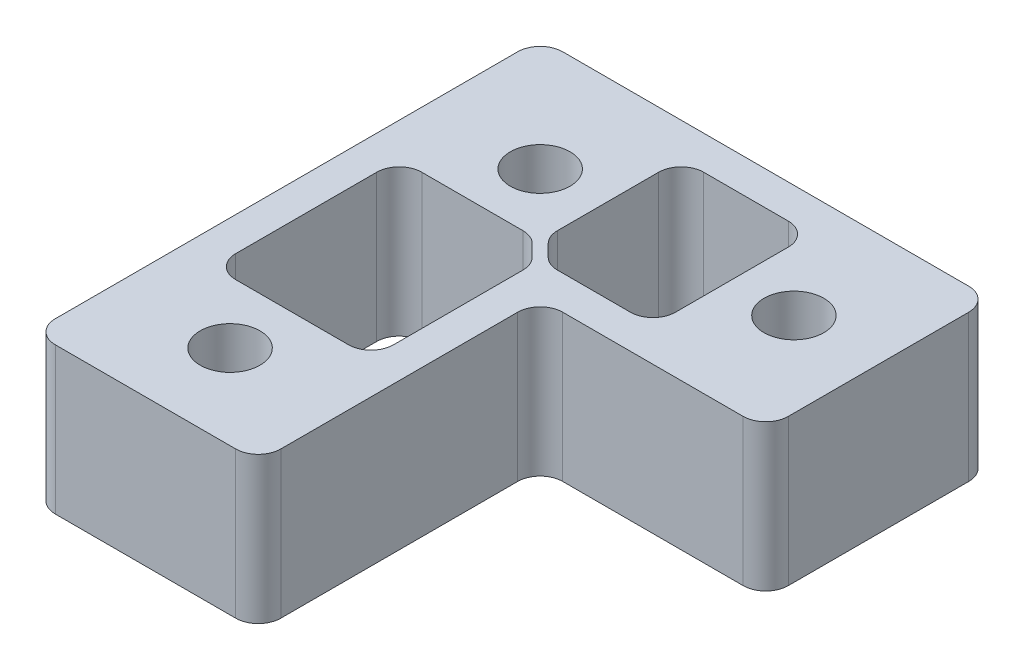
SolidWorks part; units mm, degrees
ref_plane "Front Plane" through (0, 0, 0) normal (0, 0, 1) x (1, 0, 0)
ref_plane "Top Plane" through (0, 0, 0) normal (0, 1, 0) x (1, 0, 0)
ref_plane "Right Plane" through (0, 0, 0) normal (1, 0, 0) x (0, 0, -1)
sketch "Sketch1" plane through (0, 0, 0) normal (0, 1, 0) x (1, 0, 0)
  line L0 (0, 0) -> (0, -2.65) construction
  line L2 (-10, 10) -> (-10, -35)
  line L3 (-10, -35) -> (10, -35)
  line L4 (10, -10) -> (10, -35)
  line L5 (-10, 10) -> (30, 10)
  line L7 (10, -10) -> (30, -10)
  line L8 (30, 10) -> (30, -10)
  line L9 (0, 0) -> (2.65, 0) construction
  line L10 (0, -30.15) -> (0, -35) construction
  line L11 (25.15, 0) -> (30, 0) construction
  circle A0 centre (0, 0) radius 2.65
  circle A1 centre (0, -27.5) radius 2.65
  circle A2 centre (22.5, 0) radius 2.65
  dimension "D4" = 5.3
  dimension "D1" = 20
  dimension "D2" = 45
  dimension "D3" = 40
  dimension "D5" = 7.5
extrude "Boss-Extrude1" add sketch "Sketch1" along normal blind 13
sketch "Sketch2" plane through (0, 13, 0) normal (0, 1, 0) x (1, 0, 0)
  line L0 (-7, -22) -> (-10, -22) construction
  line L1 (-7, -5.5) -> (4.7929, -5.5)
  line L2 (-7, -5.5) -> (-7, -22)
  line L3 (-7, -22) -> (7, -22)
  line L4 (7, -7.7071) -> (7, -22)
  line L5 (17, 7) -> (5.5, 7)
  line L6 (17, 7) -> (17, -7)
  line L7 (17, -7) -> (7.7071, -7)
  line L8 (5.5, 7) -> (5.5, -4.7929)
  line L9 (-10, 10) -> (-10, -35) construction
  line L10 (7, -22) -> (10, -22) construction
  line L11 (10, -35) -> (10, -10) construction
  line L12 (17, -7) -> (17, -10) construction
  line L13 (10, -10) -> (30, -10) construction
  line L14 (0, -27.5) -> (0, -22) construction
  line L15 (22.5, 0) -> (17, 0) construction
  line L16 (0, 0) -> (0, -5.5) construction
  line L17 (0, 0) -> (5.5, 0) construction
  line L18 (4.7929, -5.5) -> (7, -7.7071)
  line L19 (5.5, -4.7929) -> (7.7071, -7)
  line L20 (5.5, -4.7929) -> (4.7929, -5.5) construction
  line L21 (7.7071, -7) -> (7, -7.7071) construction
  point P26 (4.6465, -5.5)
  dimension "D1" = 3
  dimension "D2" = 5.5
  dimension "D3" = 1
  dimension "D4" = 180
extrude "Cut-Extrude1" cut sketch "Sketch2" against normal through all
fillet "Fillet1" radius 2 16 edges at (17, 6.5, 7) (7, 6.5, 22) (-7, 6.5, 22) (5.5, 6.5, -7) (-7, 6.5, 5.5) (17, 6.5, -7) (-10, 6.5, -10) (30, 6.5, -10) (30, 6.5, 10) (10, 6.5, 10) (10, 6.5, 35) (-10, 6.5, 35) (7.7071, 6.5, 7) (5.5, 6.5, 4.7929) (7, 6.5, 7.7071) (4.7929, 6.5, 5.5)
